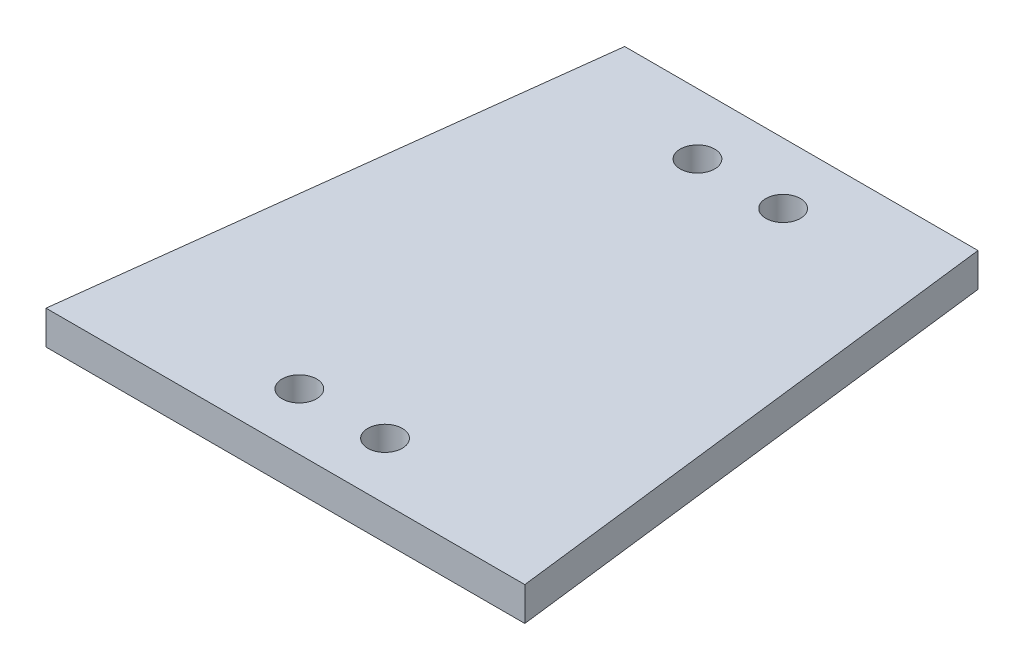
SolidWorks part; units mm, degrees
material "PET"
ref_plane "Front Plane" through (0, 0, 0) normal (0, 0, 1) x (1, 0, 0)
ref_plane "Top Plane" through (0, 0, 0) normal (0, 1, 0) x (1, 0, 0)
ref_plane "Right Plane" through (0, 0, 0) normal (1, 0, 0) x (0, 0, -1)
ref_plane "Plane1" through (0, -14, 0) normal (0, 1, 0) x (1, 0, 0)
sketch "Sketch1" plane through (0, -14, 0) normal (0, 1, 0) x (1, 0, 0)
  line L0 (-28.4185, 23.7577) -> (28.4185, 23.7577)
  line L1 (28.4185, 23.7577) -> (20.9705, 85)
  line L2 (20.9705, 85) -> (-20.9705, 85)
  line L3 (-20.9705, 85) -> (-28.4185, 23.7577)
extrude "Boss-Extrude1" add sketch "Sketch1" against normal blind 4
ref_plane "Plane2" through (0, 0, -64.665) normal (0, 0, -1) x (-1, 0, 0)
sketch "Sketch2" plane through (0, 0, -64.665) normal (0, 0, -1) x (-1, 0, 0)
  line L0 (-3.85, -30) -> (0, -30)
  line L1 (0, -30) -> (0, -18)
  line L2 (0, -18) -> (-8, -18)
  line L3 (-8, -18) -> (-8, -24)
  line L4 (-8, -24) -> (-3.85, -24)
  line L5 (-3.85, -24) -> (-3.85, -30)
  line L6 (0, -30) -> (0, -18) construction
  point P6 (0, 0)
  dimension "D1" = 6
  dimension "D2" = 6
  dimension "D3" = 3.85
  dimension "D4" = 8
revolve "Revolve1" add sketch "Sketch2" angle 360 about L6
hole_wizard "Ø4.1 (4.1) Diameter Hole1" positions "Sketch4" profile "Sketch3" hole size "Ø4.1" standard "ANSI Metric"
sketch "Sketch4" plane through (0, -14, 0) normal (0, 1, 0) x (1, 0, 0)
  point P0 (-5.085, 30.495)
  point P1 (5.085, 30.495)
  point P2 (5.085, 77.755)
  point P3 (-5.085, 77.755)
sketch "Sketch3" plane through (-5.085, -14, -30.495) normal (1, 0, 0) x (0, 0, 1)
  line L0 (0, 0) -> (0, 16)
  line L1 (0, 16) -> (2.05, 16)
  line L2 (2.05, 16) -> (2.05, 0)
  line L5 (2.05, 0) -> (0, 0)
  line L11 (0, -6.35) -> (0, 107.95) construction
  dimension "Thru Hole Dia." = 4.1
  dimension "Thru Hole Depth" = 16
sketch "Sketch5" plane through (0, -30, 0) normal (0, -1, 0) x (1, 0, 0)
  point P0 (0, -64.665)
  point P1 (0, 0)
chamfer "Chamfer1" distance 1 angle 45 2 edges at (-8, -24, -64.665) (-3.85, -30, -64.665)
